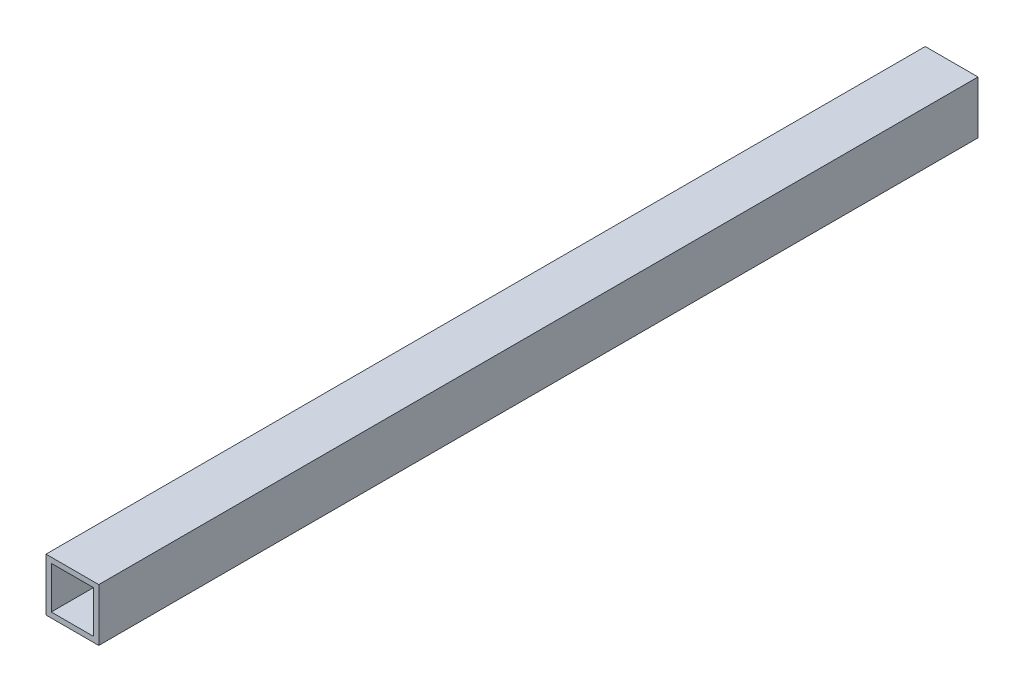
SolidWorks part; units mm, degrees
ref_plane "前视基准面" through (0, 0, 0) normal (0, 0, 1) x (1, 0, 0)
ref_plane "上视基准面" through (0, 0, 0) normal (0, 1, 0) x (1, 0, 0)
ref_plane "右视基准面" through (0, 0, 0) normal (1, 0, 0) x (0, 0, -1)
sketch "草图1" plane through (0, 0, 0) normal (0, 0, 1) x (1, 0, 0)
  line L1 (-6, 6) -> (6, 6)
  line L2 (-6, 6) -> (-6, -6)
  line L3 (-6, -6) -> (6, -6)
  line L4 (6, 6) -> (6, -6)
  line L5 (-6, 6) -> (6, -6) construction
  line L6 (-6, -6) -> (6, 6) construction
  point P0 (0, 0)
  dimension "D1" = 12
extrude "拉伸-薄壁1" add sketch "草图1" along normal blind 250 thin thin type one direction wall 1.5
